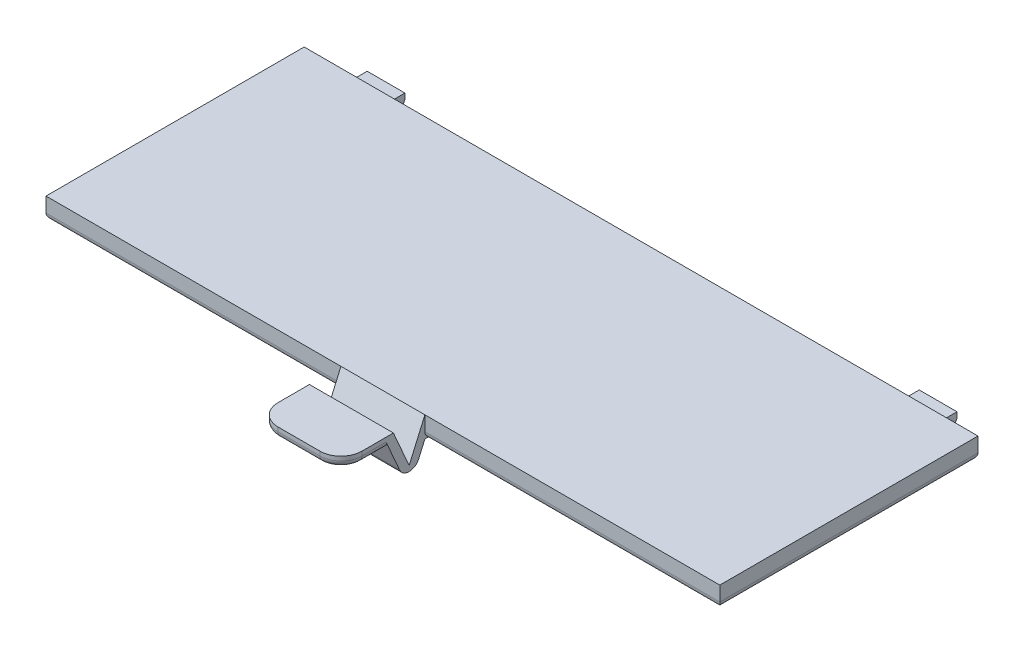
SolidWorks part; units mm, degrees
ref_plane "Alzado" through (0, 0, 0) normal (0, 0, 1) x (1, 0, 0)
ref_plane "Planta" through (0, 0, 0) normal (0, 1, 0) x (1, 0, 0)
ref_plane "Vista lateral" through (0, 0, 0) normal (1, 0, 0) x (0, 0, -1)
sketch "Croquis1" plane through (0, 0, 0) normal (0, 1, 0) x (1, 0, 0)
  line L1 (-15.7202, 9.0142) -> (16.3798, 9.0142)
  line L2 (-15.7202, 9.0142) -> (-15.7202, -3.2858)
  line L3 (-15.7202, -3.2858) -> (16.3798, -3.2858)
  line L4 (16.3798, 9.0142) -> (16.3798, -3.2858)
  dimension "D1" = 32.1
  dimension "D2" = 12.3
extrude "Saliente-Extruir1" add sketch "Croquis1" along normal blind 1
sketch "Croquis2" plane through (-6.706, 0, -9.0142) normal (0, 0, 1) x (1, 0, 0)
  line L1 (-7.0142, 0.5) -> (-5.2142, 0.5)
  line L2 (-7.0142, 0.5) -> (-7.0142, 0)
  line L3 (-7.0142, 0) -> (-5.2142, 0)
  line L4 (-5.2142, 0.5) -> (-5.2142, 0)
  line L6 (19.2858, 0.5) -> (21.0858, 0.5)
  line L7 (19.2858, 0.5) -> (19.2858, 0)
  line L8 (19.2858, 0) -> (21.0858, 0)
  line L9 (21.0858, 0.5) -> (21.0858, 0)
  line L11 (-9.0142, 1) -> (-9.0142, 0) construction
  line L12 (23.0858, 1) -> (23.0858, 0) construction
  line L13 (-9.0142, 0) -> (23.0858, 0) construction
  dimension "D1" = 1.8
  dimension "D2" = 0.5
  dimension "D3" = 2
  dimension "D4" = 2
extrude "Saliente-Extruir2" add sketch "Croquis2" against normal blind 1
ref_plane "Plano1" through (0.3298, 0, 0) normal (-1, 0, 0) x (0, 0, 1)
sketch "Croquis4" plane through (0.3298, 0, 0) normal (-1, 0, 0) x (0, 0, 1)
  line L0 (3.2858, 1) -> (3.2858, 0)
  line L1 (3.2858, 1) -> (3.2858, 0) construction
  line L2 (3.2858, 0) -> (4.0358, -1.7185)
  line L3 (4.0358, -1.7185) -> (5.004, 0.5)
  line L4 (5.004, 0.5) -> (7.2858, 0.5)
  line L5 (7.2858, 0.5) -> (7.2858, 1)
  line L6 (7.2858, 1) -> (4.7858, 1)
  line L7 (3.2858, 1) -> (4.0358, -0.7185)
  line L8 (4.0358, -0.7185) -> (4.7858, 1)
  dimension "D1" = 0.5
  dimension "D2" = 4
  dimension "D3" = 0.4
  dimension "D4" = 0.4
  dimension "D5" = 1.5
extrude "Saliente-Extruir3" add sketch "Croquis4" along normal mid plane 4
fillet "Redondeo2" radius 0.5 1 edges at (0.3298, -1.7185, 4.0358)
fillet "Redondeo3" radius 1 2 edges at (-1.6702, 0.75, 7.2858) (2.3298, 0.75, 7.2858)
fillet "Redondeo4" radius 0.3 5 edges at (-1.6702, 0.5, 5.6449) (-1.3773, 0.5, 6.9929) (2.3298, 0.5, 5.6449) (2.0369, 0.5, 6.9929) (0.3298, 0.5, 7.2858)
fillet "Redondeo6" radius 0.3 9 edges at (9.3548, 0, 3.2858) (16.3798, 0, -2.8642) (15.3798, 0, -9.0142) (13.4798, 0, -10.0142) (0.3298, 0, -9.0142) (-12.8202, 0, -10.0142) (-14.7202, 0, -9.0142) (-8.6952, 0, 3.2858) (-15.7202, 0, -2.8642)
